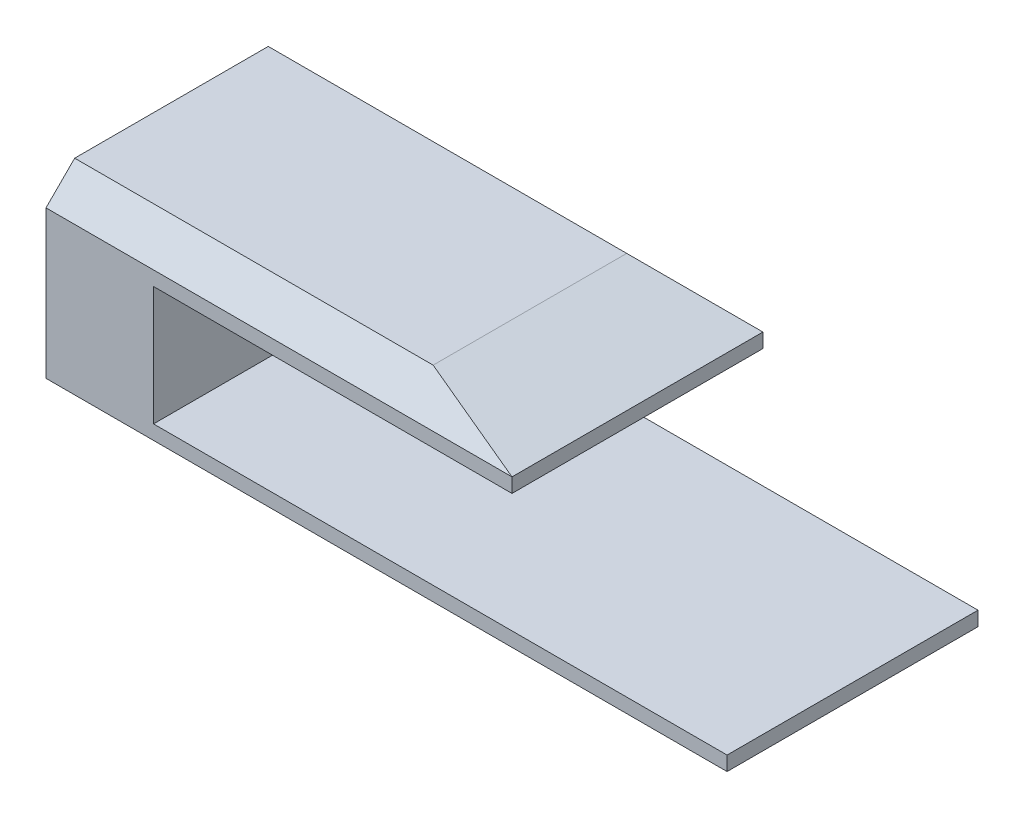
SolidWorks part; units mm, degrees
ref_plane "Спереди" through (0, 0, 0) normal (0, 0, 1) x (1, 0, 0)
ref_plane "Сверху" through (0, 0, 0) normal (0, 1, 0) x (1, 0, 0)
ref_plane "Справа" through (0, 0, 0) normal (1, 0, 0) x (0, 0, -1)
sketch "Эскиз2" plane through (0, 0, 0) normal (0, 0, 1) x (1, 0, 0)
  line L0 (0, 0) -> (65, 0)
  line L1 (65, 0) -> (65, -6)
  line L2 (65, -6) -> (15, -6)
  line L3 (15, -6) -> (15, -22.6)
  line L4 (15, -22.6) -> (95, -22.6)
  line L5 (95, -22.6) -> (95, -28.6)
  line L6 (95, -28.6) -> (0, -28.6)
  line L7 (0, -28.6) -> (0, 0)
  dimension "D1" = 15
  dimension "D2" = 80
  dimension "D3" = 50
  dimension "D4" = 6
  dimension "D5" = 16.6
  dimension "D6" = 6
  dimension "D7" = 65
  dimension "D8" = 95
  dimension "D9" = 28.6
extrude "Бобышка-Вытянуть1" add sketch "Эскиз2" along normal blind 35
sketch "Эскиз3" plane through (0, 0, 0) normal (-1, 0, 0) x (0, 0, 1)
  line L0 (0, 0) -> (35, -28.6) construction
  line L1 (35, -28.6) -> (0, -28.6) construction
  line L2 (35, 0) -> (35, -28.6) construction
  line L3 (35, 0) -> (0, -28.6) construction
  line L4 (35, 0) -> (0, 0) construction
  line L5 (0, -14.3) -> (35, -14.3) construction
  line L6 (0, 0) -> (0, -28.6) construction
  line L7 (17.5, 0) -> (17.5, -28.6) construction
  line L9 (6.8934, -14.3) -> (17.5, -24.9066)
  line L10 (17.5, -24.9066) -> (28.1066, -14.3)
  line L11 (28.1066, -14.3) -> (17.5, -3.6934)
  line L12 (17.5, -3.6934) -> (6.8934, -14.3)
  circle A0 centre (17.5, -14.3) radius 7.5 construction
  dimension "D1" = 15
extrude "Вырез-Вытянуть2" cut sketch "Эскиз3" against normal blind 3
sketch "Эскиз4" plane through (0, 0, 0) normal (-1, 0, 0) x (0, 0, 1)
  line L0 (17.5, 0) -> (17.5, -28.6) construction
  line L1 (35, 0) -> (0, 0) construction
  line L2 (35, -28.6) -> (0, -28.6) construction
  line L3 (35, -14.3) -> (0, -14.3) construction
  line L4 (35, 0) -> (35, -28.6) construction
  line L5 (0, 0) -> (0, -28.6) construction
  circle A0 centre (17.5, -14.3) radius 2.5
  dimension "D1" = 5
extrude "Вырез-Вытянуть3" cut sketch "Эскиз4" against normal up to surface (15 mm away) up to face at (15, -14.3, 17.5)
chamfer "Фаска2" distance 4 angle 45 1 edges at (15, -16.8, 17.5)
chamfer "Фаска3" distance 4 angle 45 4 edges at (47.5, -28.6, 35) (47.5, -28.6, 0) (32.5, 0, 35) (32.5, 0, 0)
chamfer "Фаска4" distance 4 distance2 15 1 edges at (65, 0, 17.5)
chamfer "Фаска5" distance 15 distance2 4 1 edges at (95, -28.6, 17.5)
